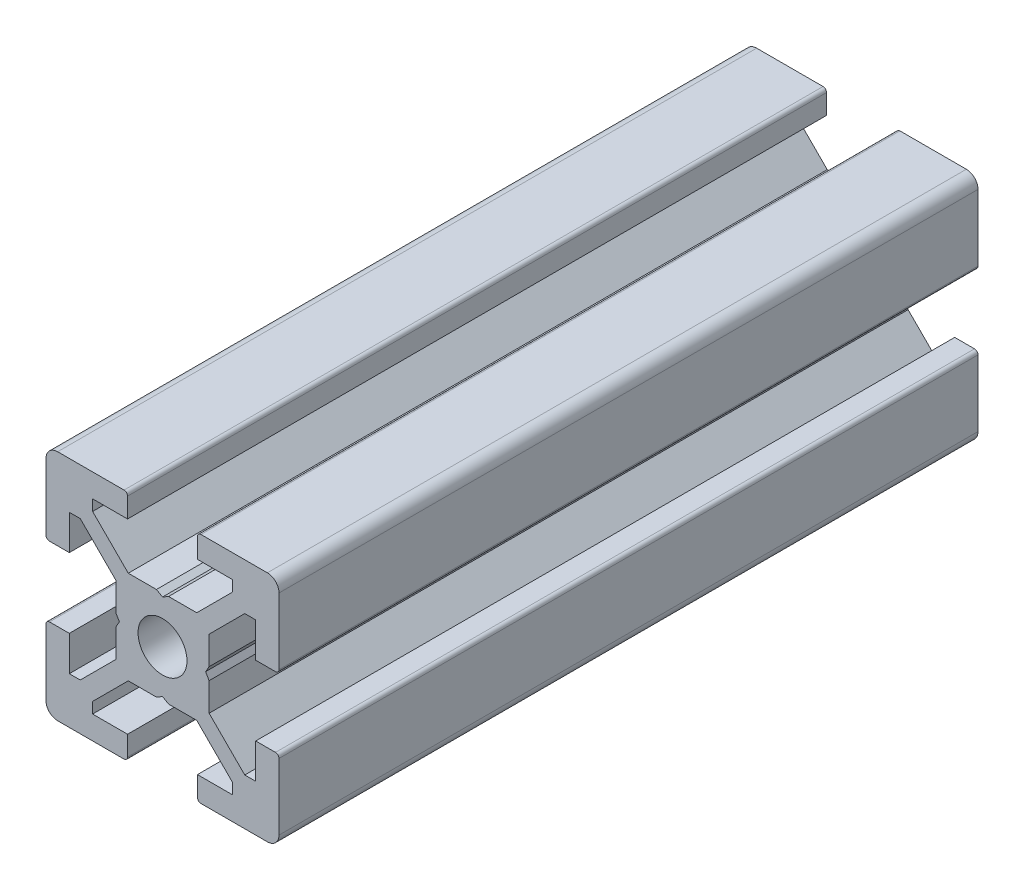
SolidWorks part; units mm, degrees
ref_plane "Front Plane" through (0, 0, 0) normal (0, 0, 1) x (1, 0, 0)
ref_plane "Top Plane" through (0, 0, 0) normal (0, 1, 0) x (1, 0, 0)
ref_plane "Right Plane" through (0, 0, 0) normal (1, 0, 0) x (0, 0, -1)
ref_plane "Plane1" through (0, 0, 0) normal (0, 0, 1) x (1, 0, 0)
sketch "Sketch1" plane through (0, 0, 0) normal (0, 0, 1) x (1, 0, 0)
  line L0 (-10, 9) -> (-10, 3.3)
  line L1 (-9.7, 3) -> (-8, 3)
  line L2 (-8, 3) -> (-8, 6)
  line L3 (-8, 6) -> (-7.0607, 6)
  line L4 (-7.0607, 6) -> (-4, 2.9393)
  line L5 (-4, 2.9393) -> (-4, 0.5196)
  line L6 (-4, 0.5196) -> (-3.7, 0)
  line L7 (-3.7, 0) -> (-4, -0.5196)
  line L8 (-4, -0.5196) -> (-4, -2.9393)
  line L9 (-4, -2.9393) -> (-7.0607, -6)
  line L10 (-7.0607, -6) -> (-8, -6)
  line L11 (-8, -6) -> (-8, -3)
  line L12 (-8, -3) -> (-9.7, -3)
  line L13 (-10, -3.3) -> (-10, -9)
  line L14 (-9, -10) -> (-3.3, -10)
  line L15 (-3, -9.7) -> (-3, -8)
  line L16 (-3, -8) -> (-6, -8)
  line L17 (-6, -8) -> (-6, -7.0607)
  line L18 (-6, -7.0607) -> (-2.9393, -4)
  line L19 (-2.9393, -4) -> (-0.5196, -4)
  line L20 (-0.5196, -4) -> (0, -3.7)
  line L21 (0, -3.7) -> (0.5196, -4)
  line L22 (0.5196, -4) -> (2.9393, -4)
  line L23 (2.9393, -4) -> (6, -7.0607)
  line L24 (6, -7.0607) -> (6, -8)
  line L25 (6, -8) -> (3, -8)
  line L26 (3, -8) -> (3, -9.7)
  line L27 (3.3, -10) -> (9, -10)
  line L28 (10, -9) -> (10, -3.3)
  line L29 (9.7, -3) -> (8, -3)
  line L30 (8, -3) -> (8, -6)
  line L31 (8, -6) -> (7.0606, -6)
  line L32 (7.0606, -6) -> (4, -2.9393)
  line L33 (4, -2.9393) -> (4, -0.5196)
  line L34 (4, -0.5196) -> (3.7, 0)
  line L35 (3.7, 0) -> (4, 0.5196)
  line L36 (4, 0.5196) -> (4, 2.9393)
  line L37 (4, 2.9393) -> (7.0607, 6)
  line L38 (7.0607, 6) -> (8, 6)
  line L39 (8, 6) -> (8, 3)
  line L40 (8, 3) -> (9.7, 3)
  line L41 (10, 3.3) -> (10, 9)
  line L42 (9, 10) -> (3.3, 10)
  line L43 (3, 9.7) -> (3, 8)
  line L44 (3, 8) -> (6, 8)
  line L45 (6, 8) -> (6, 7.0607)
  line L46 (6, 7.0607) -> (2.9393, 4)
  line L47 (2.9393, 4) -> (0.5196, 4)
  line L48 (0.5196, 4) -> (0, 3.7)
  line L49 (0, 3.7) -> (-0.5196, 4)
  line L50 (-0.5196, 4) -> (-2.9394, 4)
  line L51 (-2.9394, 4) -> (-6, 7.0606)
  line L52 (-6, 7.0606) -> (-6, 8)
  line L53 (-6, 8) -> (-3, 8)
  line L54 (-3, 8) -> (-3, 9.7)
  line L55 (-3.3, 10) -> (-9, 10)
  arc A0 (-10, 3.3) -> (-9.7, 3) centre (-9.7, 3.3) ccw
  arc A1 (-9.7, -3) -> (-10, -3.3) centre (-9.7, -3.3) ccw
  arc A2 (-10, -9) -> (-9, -10) centre (-9, -9) ccw
  arc A3 (-3.3, -10) -> (-3, -9.7) centre (-3.3, -9.7) ccw
  arc A4 (3, -9.7) -> (3.3, -10) centre (3.3, -9.7) ccw
  arc A5 (9, -10) -> (10, -9) centre (9, -9) ccw
  arc A6 (10, -3.3) -> (9.7, -3) centre (9.7, -3.3) ccw
  arc A7 (9.7, 3) -> (10, 3.3) centre (9.7, 3.3) ccw
  arc A8 (10, 9) -> (9, 10) centre (9, 9) ccw
  arc A9 (3.3, 10) -> (3, 9.7) centre (3.3, 9.7) ccw
  arc A10 (-3, 9.7) -> (-3.3, 10) centre (-3.3, 9.7) ccw
  arc A11 (-9, 10) -> (-10, 9) centre (-9, 9) ccw
extrude "Boss-Extrude1" add sketch "Sketch1" against normal blind 60
ref_plane "Plane2" through (0, 0, 0) normal (1, 0, 0) x (0, 0, -1)
sketch "Sketch2" plane through (0, 0, 0) normal (1, 0, 0) x (0, 0, -1)
  line L0 (0, 0) -> (0, 2.1)
  line L1 (0, 2.1) -> (400, 2.1)
  line L2 (400, 2.1) -> (400, 0)
  line L3 (400, 0) -> (0, 0)
  line L4 (400, 0) -> (0, 0) construction
revolve "Cut-Revolve1" cut sketch "Sketch2" angle 360 about L4
